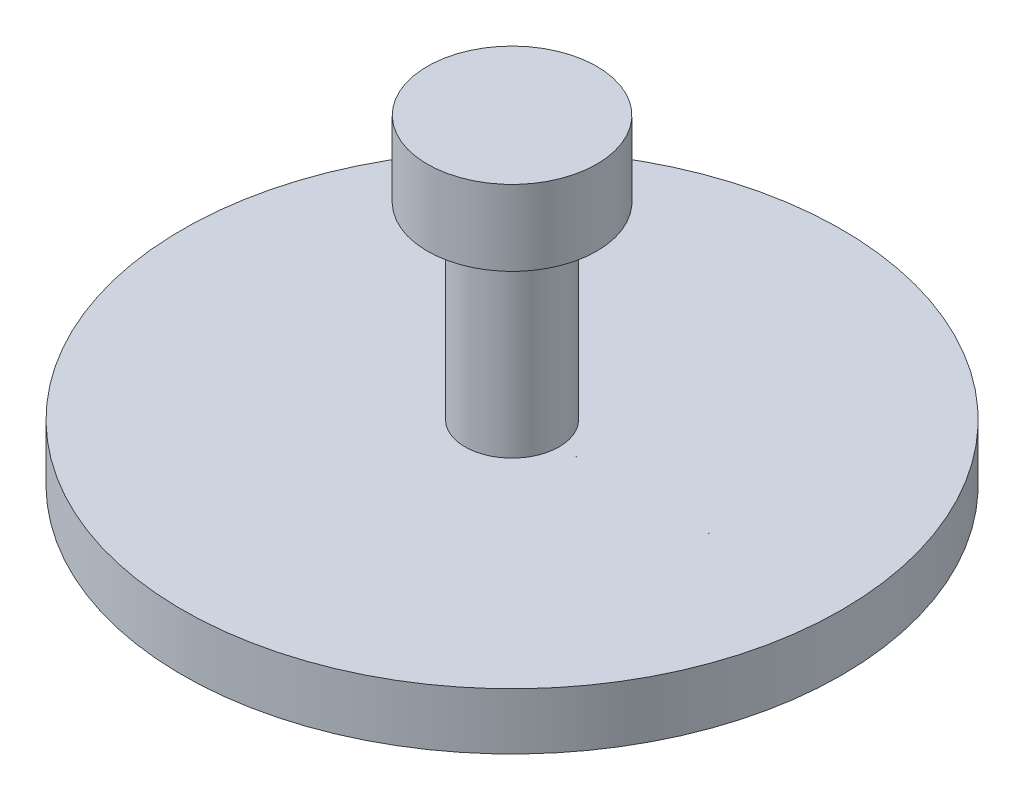
SolidWorks part; units mm, degrees
material "Plain Carbon Steel"
ref_plane "Front Plane" through (0, 0, 0) normal (0, 0, 1) x (1, 0, 0)
ref_plane "Top Plane" through (0, 0, 0) normal (0, 1, 0) x (1, 0, 0)
ref_plane "Right Plane" through (0, 0, 0) normal (1, 0, 0) x (0, 0, -1)
sketch "Sketch1" plane through (0, 0, 0) normal (0, 0, 1) x (1, 0, 0)
  line L0 (0, 0) -> (0, 17) construction
  line L1 (0, 0) -> (17.5, 0)
  line L2 (17.5, 0) -> (17.5, 3)
  line L3 (17.5, 3) -> (2.5, 3)
  line L4 (2.5, 3) -> (2.5, 13)
  line L5 (2.5, 13) -> (4.5, 13)
  line L6 (4.5, 13) -> (4.5, 17)
  line L7 (4.5, 17) -> (0, 17)
  line L8 (0, 17) -> (0, 0)
revolve "Revolve1" add sketch "Sketch1" angle 360 about L0
